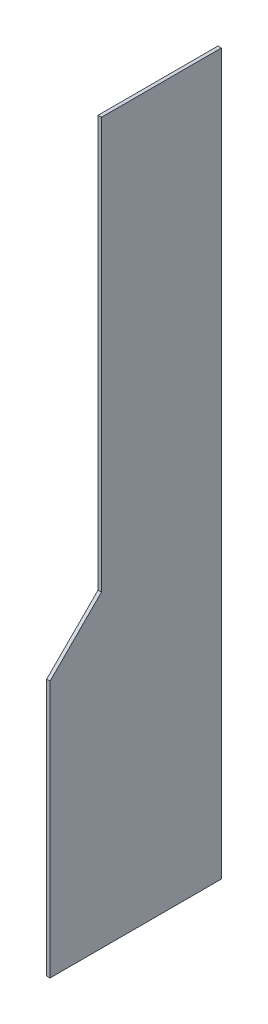
SolidWorks part; units mm, degrees
material "Бук"
ref_plane "Спереди" through (0, 0, 0) normal (0, 0, 1) x (1, 0, 0)
ref_plane "Сверху" through (0, 0, 0) normal (0, 1, 0) x (1, 0, 0)
ref_plane "Справа" through (0, 0, 0) normal (1, 0, 0) x (0, 0, -1)
sketch "Эскиз1" plane through (0, 0, 0) normal (1, 0, 0) x (0, 0, -1)
  line L0 (0, 750) -> (150, 900)
  line L1 (0, 0) -> (500, 0)
  line L2 (0, 0) -> (0, 750)
  line L3 (250, 2100) -> (500, 2100)
  line L4 (500, 0) -> (500, 2100)
  line L5 (150, 900) -> (150, 2000)
  line L7 (250, 2100) -> (150, 2100)
  line L8 (150, 2100) -> (150, 2000)
  dimension "D1" = 500
  dimension "D2" = 2100
  dimension "D3" = 750
  dimension "D4" = 150
  dimension "D5" = 150
extrude "Бобышка-Вытянуть1" add sketch "Эскиз1" along normal blind 10
